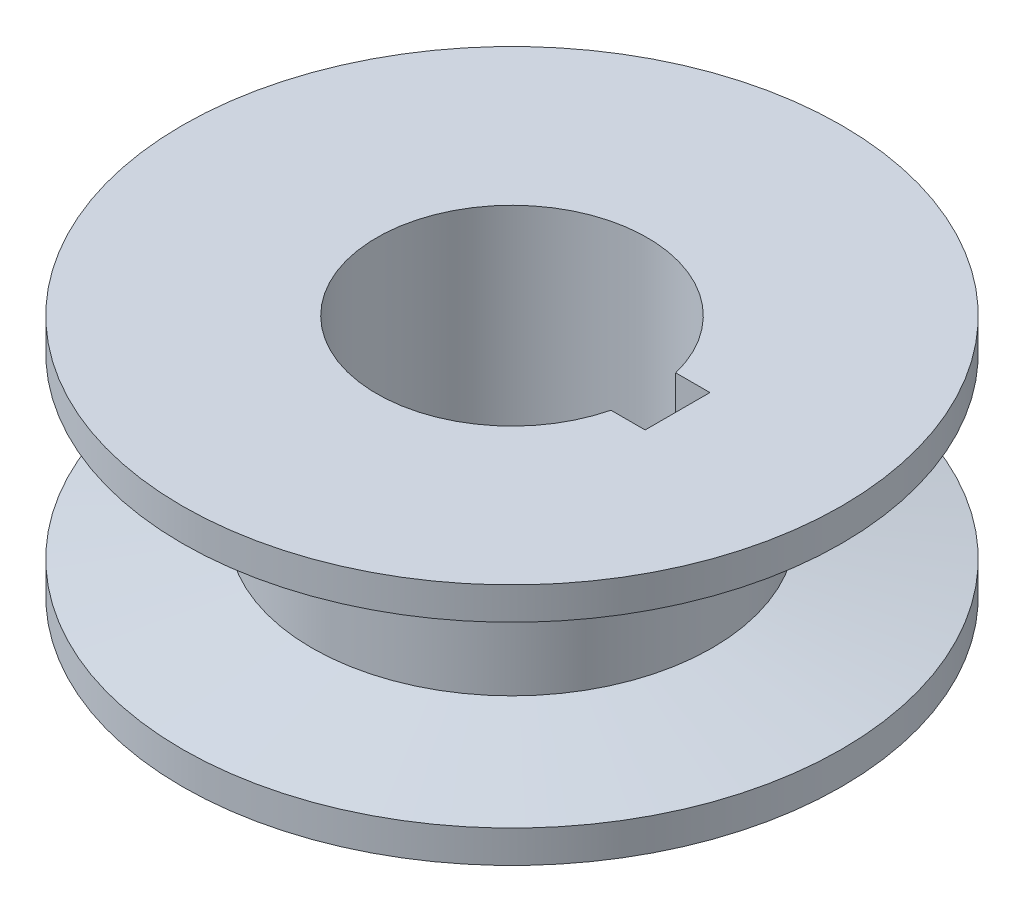
SolidWorks part; units mm, degrees
ref_plane "Front Plane" through (0, 0, 0) normal (0, 0, 1) x (1, 0, 0)
ref_plane "Top Plane" through (0, 0, 0) normal (0, 1, 0) x (1, 0, 0)
ref_plane "Right Plane" through (0, 0, 0) normal (1, 0, 0) x (0, 0, -1)
sketch "Sketch1" plane through (0, 0, 0) normal (0, 0, 1) x (1, 0, 0)
  line L0 (20.35, 5.5) -> (12.35, 4.0894)
  line L1 (8.35, 7.5) -> (20.35, 7.5)
  line L2 (8.35, 7.5) -> (8.35, -7.5)
  line L3 (8.35, -7.5) -> (20.35, -7.5)
  line L4 (20.35, 7.5) -> (20.35, 5.5)
  line L5 (12.35, 4.0894) -> (12.35, -4.0894)
  line L6 (12.35, -4.0894) -> (20.35, -5.5)
  line L7 (0, -1000) -> (0, 49000) construction
  line L8 (20.35, -5.5) -> (20.35, -7.5)
  point P4 (8.35, 0)
  dimension "D1" = 8.35
  dimension "D2" = 12
  dimension "D3" = 15
  dimension "D4" = 100
  dimension "D5" = 100
  dimension "D6" = 2
  dimension "D7" = 2
  dimension "D8" = 8
revolve "Revolve1" add sketch "Sketch1" angle 360 about L7
sketch "Sketch2" plane through (0, 7.5, 0) normal (0, 1, 0) x (1, 0, 0)
  line L1 (10.2169, 2) -> (0, 2)
  line L2 (10.2169, 2) -> (10.2169, -2)
  line L3 (10.2169, -2) -> (0, -2)
  line L4 (0, 2) -> (0, -2)
  point P4 (0, 0)
  dimension "D1" = 4
  dimension "D2" = 10.2169
extrude "Cut-Extrude1" cut sketch "Sketch2" against normal up to surface (15 mm away) up to face at (20.35, -7.5, 0)
